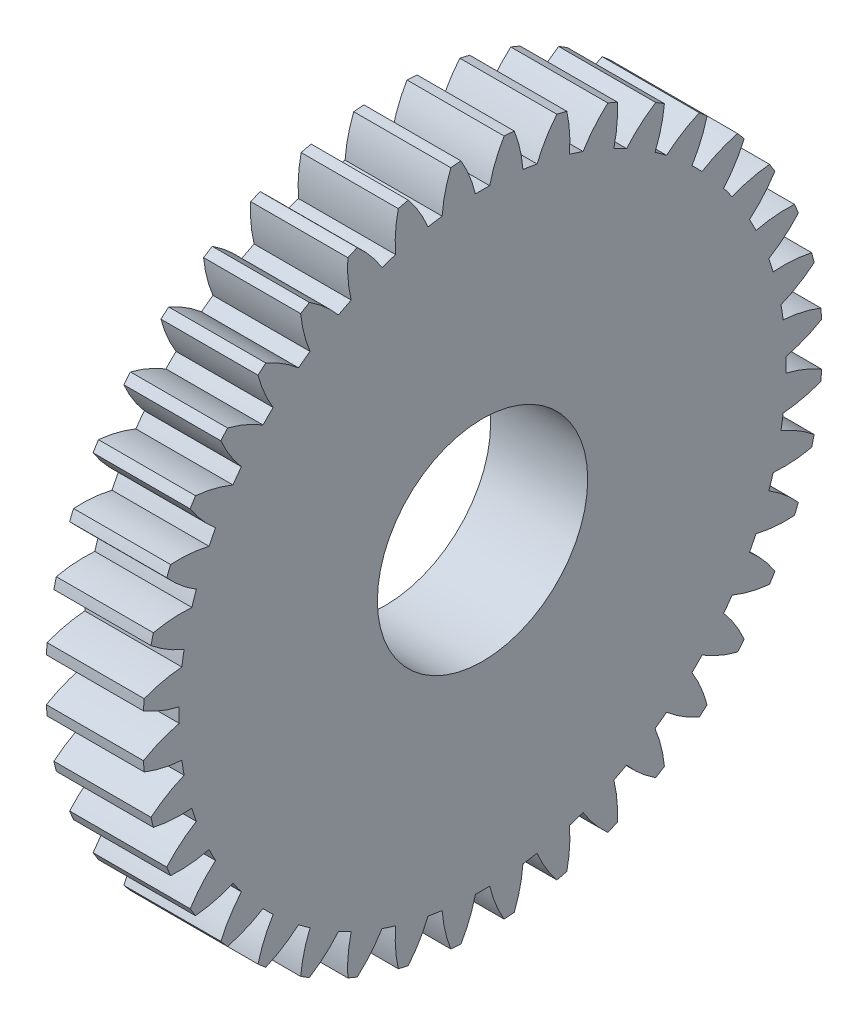
SolidWorks part; units mm, degrees
ref_plane "Plane1" through (0, 0, 0) normal (0, 0, 1) x (1, 0, 0)
ref_plane "Plane2" through (0, 0, 0) normal (0, 1, 0) x (1, 0, 0)
ref_plane "Plane3" through (0, 0, 0) normal (1, 0, 0) x (0, 0, -1)
sketch "HoldingSke" plane through (0, 0, 0) normal (0, 1, 0) x (1, 0, 0)
  line L0 (0, 0) -> (0.383, -0.3214)
  line L1 (-15, 0) -> (100, 0) construction
  line L2 (0, 0) -> (-2.1039, 2.3779)
  line L3 (0, 0) -> (-11.863, 4.5341)
  line L4 (0, 0) -> (6.6156, 5.5511)
  line L5 (0, 0) -> (-46.8476, -17.4728)
  line L6 (0, 0) -> (-9.9476, -6.7116)
  line L7 (-2.1039, 2.3779) -> (8.6586, 51.2059)
  line L8 (-76.2, 54.61) -> (-72.9, 54.61)
  line L9 (-71.009, 38.7566) -> (-53.1078, 45.2721)
  line L10 (-76.2, 71.12) -> (104.1128, 71.12)
  line L11 (0, 0) -> (-12, 0)
  line L12 (-76.2, 101.6) -> (-76.133, 101.6)
  line L13 (24.9733, 27.94) -> (52.9518, 28.4284)
  line L14 (24.9733, 27.94) -> (24.9743, 27.94)
  line L15 (24.9733, 27.94) -> (100.4006, 29.5858)
  line L16 (-63.627, -2) -> (-12.827, -2)
  circle A0 centre (0, 0) radius 13
  circle A1 centre (0, 0) radius 37.499
  circle A2 centre (0, 0) radius 37.5
  circle A3 centre (0, 0) radius 13
  dimension "MHD" = 74.998
  dimension "Hub_dia" = 75
  dimension "Bore" = 26
  dimension "MBD" = 26
  dimension "Num_teeth" = 40
  dimension "Pitch" = 0.5
  dimension "Overall_len" = 50
  dimension "Show_teeth" = 40
  dimension "Thickness" = 12
  dimension "OAL" = 50.0001
  dimension "T_dim" = 3.3
  dimension "Ap" = 20
  dimension "H" = 19.05
  dimension "Pitch_radius" = 180.3128
  dimension "Width" = 12
  dimension "Backlash" = 0.067
  dimension "Addendum_fac" = 1
  dimension "Dedendum_fac" = 1.25
  dimension "Clearance_fac" = 0.25
  dimension "Dedendum_add" = 0.001
  dimension "Module" = 2
sketch "BasProSke" plane through (0, 0, 0) normal (0, 1, 0) x (1, 0, 0)
  line L0 (-10, 0) -> (60, 0) construction
  line L1 (0, 0) -> (0, 42)
  line L2 (0, 0) -> (12, 0)
  line L3 (12, 0) -> (12, 42)
  line L4 (12, 42) -> (0, 42)
  dimension "Thickness" = 12
  dimension "Diameter" = 84
revolve "Base-Revolve" add sketch "BasProSke" angle 360 about L0
sketch "TooCutSke" plane through (0, 0, 0) normal (1, 0, 0) x (0, 0, -1)
  line L1 (0, 0) -> (0, 107) construction
  line L2 (0, 0) -> (-1.6876, 39.9644) construction
  line L3 (0, 0) -> (-6.2726, 79.7007) construction
  line L4 (-1.6876, 39.9644) -> (-3.1363, 39.8504) construction
  arc A0 (0.8828, 37.4886) -> (-0.8828, 37.4886) centre (0, 0) ccw
  arc A1 (2.6784, 41.94) -> (-2.6784, 41.94) centre (0, 0) ccw
  circle A2 centre (0, 0) radius 40 construction
  circle A3 centre (0, 0) radius 37.5877 construction
  arc A4 (-0.8828, 37.4886) -> (-2.6784, 41.94) centre (-16.451, 33.7965) ccw
  arc A5 (2.6784, 41.94) -> (0.8828, 37.4886) centre (16.451, 33.7965) ccw
  dimension "Root_dia" = 74.998
  dimension "Overcut_dia" = 84.0508
  dimension "Pitch_dia" = 80
  dimension "Base_dia" = 75.1754
  dimension "Flank_rad" = 16
  dimension "Half_ang" = 4.5
  dimension "Half_CT" = 1.4531
extrude "ToothCut" cut sketch "TooCutSke" along normal through all
fillet "Breaks" [suppressed] radius 0.04
fillet "RootFillets" [suppressed] radius 0.501
pattern_circular "TeethCuts" count 40 every 9 about axis through (-10, 0, 0) along (1, 0, 0) of "ToothCut", "RootFillets", "Breaks"
sketch "HubNeaOneSke" plane through (0, 0, 0) normal (-1, 0, 0) x (0, 0, 1)
  circle A0 centre (0, 0) radius 37.499
  dimension "Diameter" = 74.998
extrude "HubNearOne" [suppressed] add sketch "HubNeaOneSke" along normal blind 38.0001
sketch "HubNeaBotSke" plane through (0, 0, 0) normal (-1, 0, 0) x (0, 0, 1)
  circle A0 centre (0, 0) radius 37.499
  dimension "Diameter" = 74.998
extrude "HubNearBoth" [suppressed] add sketch "HubNeaBotSke" along normal blind 19
ref_plane "FarPln" through (12, 0, 0) normal (1, 0, 0) x (0, 0, -1)
sketch "HubFarSke" plane through (12, 0, 0) normal (1, 0, 0) x (0, 0, -1)
  circle A0 centre (0, 0) radius 37.499
  dimension "Diameter" = 74.998
extrude "HubFar" [suppressed] add sketch "HubFarSke" along normal blind 19
sketch "BorSke" plane through (0, 0, 0) normal (1, 0, 0) x (0, 0, -1)
  circle A0 centre (0, 0) radius 13
  dimension "Diameter" = 26
extrude "Bore" cut sketch "BorSke" along normal mid plane 100.0001
sketch "KeySke" plane through (0, 0, 0) normal (1, 0, 0) x (0, 0, -1)
  line L0 (-4, 0) -> (-4, 16.3)
  line L1 (-4, 16.3) -> (4, 16.3)
  line L2 (4, 16.3) -> (4, 0)
  line L3 (0, 0) -> (0, 34) construction
  line L4 (-4, 0) -> (4, 0)
  dimension "Offset" = 16.3
  dimension "Width" = 8
extrude "Keyway" [suppressed] cut sketch "KeySke" along normal mid plane 100.0001
pattern_circular "Keyway2" [suppressed] count 2 every 90 about axis through (-10, 0, 0) along (1, 0, 0)
equation "' \"Module@HoldingSke\" = 6.35"
equation "' \"Num_teeth@HoldingSke\" = 12"
equation "' \"Ap@HoldingSke\" =  20"
equation "' \"Ap@HoldingSke\" = 20"
equation "' \"Width@HoldingSke\" = 0.5 * 25.4"
equation "' \"Hub_dia@HoldingSke\"= 1 * 25.4"
equation "' \"Hub_dia@HoldingSke\" = 1 * 25.4"
equation "' \"Overall_len@HoldingSke\" = 1.0 * 25.4"
equation "' \"Bore@HoldingSke\" = 0.75 * 25.4"
equation "' \"T_dim@HoldingSke\" = 0.1 * 25.4"
equation "' \"Width@KeySke\" = 0.25 * 25.4"
equation "' \"Show_teeth@HoldingSke\" = 13"
equation "' \"Backlash@HoldingSke\" = 0.009 * 25.4"
equation "' \"Addendum_fac@HoldingSke\" = 1.0"
equation "' \"Dedendum_fac@HoldingSke\" = 1.25"
equation "' \"Dedendum_add@HoldingSke\" = 0.00005 * 25.4"
equation "' \"Clearance_fac@HoldingSke\" = 0.25"
equation "\"Pitch@HoldingSke\" = 1 / \"Module@HoldingSke\""
equation "\"Overcut_dia@TooCutSke\" = (\"Num_teeth@HoldingSke\" + 2 * \"Addendum_fac@HoldingSke\") / \"Pitch@HoldingSke\" + 0.002 * 25.4"
equation "\"Pitch_dia@TooCutSke\" = \"Num_teeth@HoldingSke\" / \"Pitch@HoldingSke\""
equation "\"Base_dia@TooCutSke\" = \"Num_teeth@HoldingSke\" / \"Pitch@HoldingSke\" * cos((\"Ap@HoldingSke\"  * 3.14159265 / 180))"
equation "\"Root_dia@TooCutSke\" = (\"Num_teeth@HoldingSke\" + 2) / \"Pitch@HoldingSke\" - 2 * (\"Addendum_fac@HoldingSke\" + \"Dedendum_fac@HoldingSke\") / \"Pitch@HoldingSke\" - \"Dedendum_add@HoldingSke\" * 2"
equation "\"Half_ang@TooCutSke\" = 180 / \"Num_teeth@HoldingSke\""
equation "\"Half_CT@TooCutSke\" = \"Num_teeth@HoldingSke\" / \"Pitch@HoldingSke\" * sin((3.14159265 / 2 / \"Num_teeth@HoldingSke\")) / 2 - 7 * \"Backlash@HoldingSke\" / 4"
equation "\"Flank_rad@TooCutSke\" = \"Num_teeth@HoldingSke\" / \"Pitch@HoldingSke\" / 5"
equation "\"Radius@RootFillets\" = \"Clearance_fac@HoldingSke\" / \"Pitch@HoldingSke\" + \"Dedendum_add@HoldingSke\""
equation "\"Break_rad@Breaks\" = 0.02 / \"Pitch@HoldingSke\""
equation "\"Thickness@HoldingSke\" = \"Width@HoldingSke\""
equation "\"OAL@HoldingSke\" = \"Thickness@HoldingSke\""
equation "\"MHD@HoldingSke\" = (\"Num_teeth@HoldingSke\" + 2) / \"Pitch@HoldingSke\" - 2 * (\"Addendum_fac@HoldingSke\" + \"Dedendum_fac@HoldingSke\")  / \"Pitch@HoldingSke\" - \"Dedendum_add@HoldingSke\" * 2"
equation "\"MBD@HoldingSke\" = (\"Num_teeth@HoldingSke\" + 2) / \"Pitch@HoldingSke\" - 2 * (\"Addendum_fac@HoldingSke\" + \"Dedendum_fac@HoldingSke\")  / \"Pitch@HoldingSke\" - \"Dedendum_add@HoldingSke\" * 2 - 0.002 * 25.4"
equation "\"MHD@HoldingSke\" = ((sgn( \"MHD@HoldingSke\" - \"Hub_dia@HoldingSke\" )-1)*( \"MHD@HoldingSke\" - \"Hub_dia@HoldingSke\" ))/-2+ \"Hub_dia@HoldingSke\""
equation "\"MBD@HoldingSke\" = ((sgn( \"MBD@HoldingSke\" - \"Bore@HoldingSke\" )-1)*( \"MBD@HoldingSke\" - \"Bore@HoldingSke\" ))/-2+ \"Bore@HoldingSke\""
equation "\"OAL@HoldingSke\" = ((sgn( \"OAL@HoldingSke\" - \"Overall_len@HoldingSke\" )+1)*( \"OAL@HoldingSke\" - \"Overall_len@HoldingSke\" ))/2 + \"Overall_len@HoldingSke\" + 0.000002 * 25.4"
equation "\"Num_teeth@TeethCuts\" = int( \"Show_teeth@HoldingSke\" ) + 1"
equation "\"Num_teeth@TeethCuts\" = ((sgn( \"Num_teeth@TeethCuts\" - \"Num_teeth@HoldingSke\" )-1)*( \"Num_teeth@TeethCuts\" - \"Num_teeth@HoldingSke\" ))/-2+ \"Num_teeth@HoldingSke\""
equation "\"Num_teeth@TeethCuts\" = ((sgn( \"Num_teeth@TeethCuts\" - 2.0)+1)*( \"Num_teeth@TeethCuts\" - 2.0))/2 +2.0"
equation "\"Angle@TeethCuts\" = 360.0 / \"Num_teeth@HoldingSke\""
equation "\"Diameter@BasProSke\" = (\"Num_teeth@HoldingSke\" + 2 * \"Addendum_fac@HoldingSke\") / \"Pitch@HoldingSke\""
equation "\"Thickness@BasProSke\"  = \"Thickness@HoldingSke\""
equation "' \"Fillet_rad@BasProSke\" =  \"Thickness@HoldingSke\" * 0.05"
equation "' \"Fillet_rad@BasProSke\" = \"Thickness@HoldingSke\" * 0.05"
equation "\"MHD@HoldingSke\" = ((sgn( \"MHD@HoldingSke\" - \"Root_dia@TooCutSke\" )-1)*( \"MHD@HoldingSke\" - \"Root_dia@TooCutSke\" ))/-2+ \"Root_dia@TooCutSke\""
equation "\"Diameter@HubNeaOneSke\" = \"MHD@HoldingSke\""
equation "\"Length@HubNearOne\" = \"OAL@HoldingSke\" - \"Thickness@BasProSke\""
equation "\"Diameter@HubNeaBotSke\" = \"MHD@HoldingSke\""
equation "\"Length@HubNearBoth\" = ( \"OAL@HoldingSke\" - \"Thickness@BasProSke\" ) / 2.0"
equation "\"Thickness@FarPln\" = \"Thickness@BasProSke\""
equation "\"Diameter@HubFarSke\" = \"MHD@HoldingSke\""
equation "\"Length@HubFar\" = ( \"OAL@HoldingSke\" - \"Thickness@BasProSke\" ) / 2.0"
equation "\"Diameter@BorSke\" = \"MBD@HoldingSke\""
equation "\"D1@Bore\" = \"OAL@HoldingSke\" * 2.0"
equation "\"D1@Keyway\" = \"OAL@HoldingSke\" * 2.0"
equation "\"Offset@KeySke\" = \"T_dim@HoldingSke\" + \"MBD@HoldingSke\" / 2.0"
